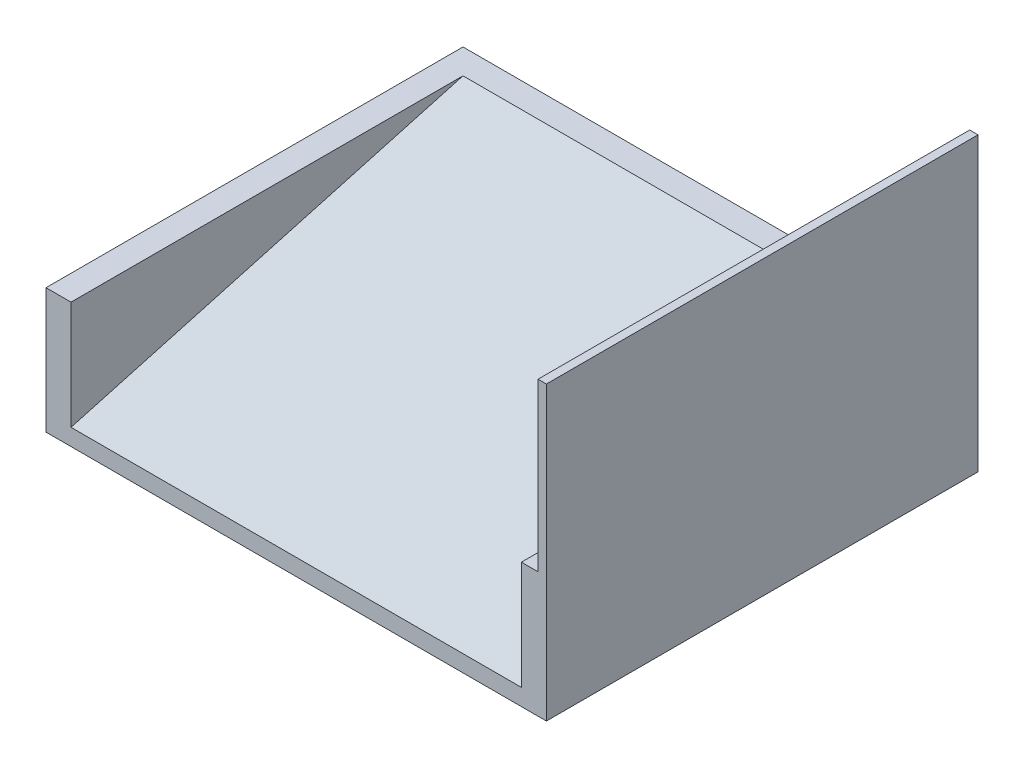
SolidWorks part; units mm, degrees
ref_plane "Front Plane" through (0, 0, 0) normal (0, 0, 1) x (1, 0, 0)
ref_plane "Top Plane" through (0, 0, 0) normal (0, 1, 0) x (1, 0, 0)
ref_plane "Right Plane" through (0, 0, 0) normal (1, 0, 0) x (0, 0, -1)
sketch "Sketch1" plane through (0, 0, 0) normal (0, 1, 0) x (1, 0, 0)
  line L1 (0, 0) -> (60, 0)
  line L2 (0, 0) -> (0, 50)
  line L3 (0, 50) -> (60, 50)
  line L4 (60, 0) -> (60, 50)
  dimension "D1" = 50
  dimension "D2" = 60
extrude "Boss-Extrude1" add sketch "Sketch1" along normal blind 2
sketch "Sketch2" plane through (0, 2, 0) normal (0, 1, 0) x (1, 0, 0)
  line L0 (60, 0) -> (60, 50)
  line L1 (60, 50) -> (0, 50)
  line L2 (0, 50) -> (0, 0)
  line L3 (0, 0) -> (3, 0)
  line L4 (0, 0) -> (60, 0) construction
  line L5 (3, 0) -> (3, 47)
  line L6 (3, 47) -> (57, 47)
  line L7 (57, 47) -> (57, 0)
  line L8 (57, 0) -> (60, 0)
  dimension "D1" = 3
  dimension "D2" = 3
  dimension "D3" = 3
extrude "Boss-Extrude2" add sketch "Sketch2" along normal blind 13
sketch "Sketch3" plane through (0, 0, -50) normal (0, 0, -1) x (-1, 0, 0)
  line L0 (-60, 0) -> (0, 0) construction
  line L1 (-60, 15) -> (-51, 15)
  line L2 (-60, 15) -> (-60, 0)
  line L3 (-60, 0) -> (-51, 0)
  line L4 (-51, 15) -> (-51, 0)
  dimension "D1" = 9
extrude "Boss-Extrude3" add sketch "Sketch3" along normal blind 1.75
fillet "Fillet1" radius 1.5 1 edges at (51, 7.5, -50)
sketch "Sketch4" plane through (0, 0, -50) normal (0, 0, -1) x (-1, 0, 0)
  line L0 (-49.5, 15) -> (0, 15) construction
  line L1 (-49.5, 15) -> (-49.5, 0) construction
  circle A0 centre (-45, 5.6) radius 2.005
  circle A1 centre (-35, 5.6) radius 2.005
  circle A2 centre (-25, 5.6) radius 2.005
  circle A3 centre (-15, 5.6) radius 2.005
  dimension "D1" = 4.01
  dimension "D4" = 4.01
  dimension "D5" = 4.01
  dimension "D6" = 4.01
  dimension "D7" = 9.4
  dimension "D11" = 9.4
  dimension "D12" = 9.4
  dimension "D2" = 9.4
  dimension "D3" = 4.5
  dimension "D8" = 10
  dimension "D9" = 10
  dimension "D10" = 10
extrude "Cut-Extrude1" cut sketch "Sketch4" against normal up to next
sketch "Sketch5" plane through (0, 15, 0) normal (0, 1, 0) x (1, 0, 0)
  line L0 (51, 51.75) -> (60, 51.75) construction
  line L1 (60, 0) -> (59, 0)
  line L2 (60, 0) -> (60, 51.75)
  line L3 (60, 51.75) -> (59, 51.75)
  line L4 (59, 0) -> (59, 51.75)
  dimension "D1" = 1
extrude "Boss-Extrude4" add sketch "Sketch5" along normal blind 20
sketch "Sketch6" plane through (0, 0, 0) normal (0, 0, 1) x (1, 0, 0)
  line L0 (0, 0) -> (60, 0) construction
  line L1 (3, 2) -> (57, 2)
  line L2 (3, 2) -> (3, 0)
  line L3 (3, 0) -> (57, 0)
  line L4 (57, 2) -> (57, 0)
extrude "Cut-Extrude2" cut sketch "Sketch6" against normal blind 47
sketch "Sketch7" plane through (3, 0, 0) normal (1, 0, 0) x (0, 0, -1)
  line L0 (0, 2) -> (0, 0)
  line L1 (0, 15) -> (0, 0) construction
  line L2 (0, 0) -> (2, 0)
  line L3 (47, 0) -> (0, 0) construction
  line L4 (2, 0) -> (47, 13)
  line L5 (47, 15) -> (47, 0) construction
  line L6 (47, 13) -> (47, 15)
  line L7 (47, 15) -> (0, 2)
  dimension "D1" = 2
  dimension "D2" = 2
  dimension "D3" = 2
extrude "Boss-Extrude5" add sketch "Sketch7" along normal up to next
